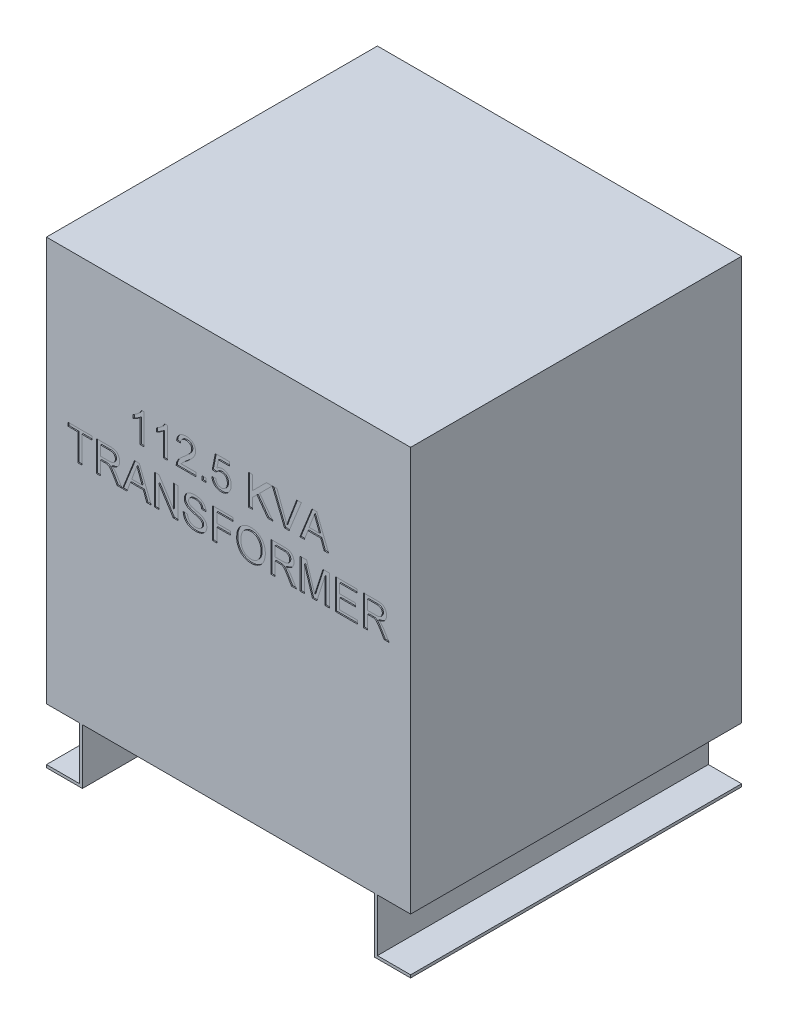
SolidWorks part; units mm, degrees
ref_plane "Front" through (0, 0, 0) normal (0, 0, 1) x (1, 0, 0)
ref_plane "Top" through (0, 0, 0) normal (0, 1, 0) x (1, 0, 0)
ref_plane "Right" through (0, 0, 0) normal (1, 0, 0) x (0, 0, -1)
sketch "Sketch1" plane through (0, 0, 0) normal (0, 1, 0) x (1, 0, 0)
  line L1 (-417.83, 379.73) -> (417.83, 379.73)
  line L2 (-417.83, 379.73) -> (-417.83, -379.73)
  line L3 (-417.83, -379.73) -> (417.83, -379.73)
  line L4 (417.83, 379.73) -> (417.83, -379.73)
  line L5 (-417.83, 379.73) -> (417.83, -379.73) construction
  line L6 (-417.83, -379.73) -> (417.83, 379.73) construction
  point P0 (0, 0)
  dimension "D1" = 835.66
  dimension "D2" = 759.46
extrude "Boss-Extrude1" add sketch "Sketch1" along normal blind 1054.608
sketch "Sketch2" plane through (0, 0, 379.73) normal (0, 0, 1) x (1, 0, 0)
  line L0 (0, 0) -> (0, 63.5) construction
  line L1 (-417.83, 0) -> (417.83, 0) construction
  line L2 (-335.28, 127) -> (335.28, 127)
  line L3 (-335.28, 127) -> (-335.28, 0)
  line L4 (-335.28, 0) -> (335.28, 0)
  line L5 (335.28, 127) -> (335.28, 0)
  line L6 (-335.28, 127) -> (335.28, 0) construction
  line L7 (-335.28, 0) -> (335.28, 127) construction
  line L8 (-417.83, 1054.608) -> (-417.83, 0) construction
  line L9 (-417.83, 6.35) -> (-341.63, 6.35)
  line L10 (-417.83, 6.35) -> (-417.83, 127)
  line L11 (-417.83, 127) -> (-341.63, 127)
  line L12 (-341.63, 6.35) -> (-341.63, 127)
  line L13 (417.83, 1054.608) -> (417.83, 0) construction
  line L14 (417.83, 6.35) -> (341.63, 6.35)
  line L15 (417.83, 6.35) -> (417.83, 127)
  line L16 (417.83, 127) -> (341.63, 127)
  line L17 (341.63, 6.35) -> (341.63, 127)
  line L18 (-417.83, 6.35) -> (-417.83, 0) construction
  line L19 (-341.63, 6.35) -> (-335.28, 6.35) construction
  line L20 (341.63, 6.35) -> (335.28, 6.35) construction
  dimension "D1" = 6.35
  dimension "D2" = 76.2
  dimension "D3" = 127
extrude "Cut-Extrude1" cut sketch "Sketch2" against normal through all
sketch "Sketch3" plane through (0, 0, 379.73) normal (0, 0, 1) x (1, 0, 0)
  line L0 (-417.83, 749.808) -> (417.83, 749.808) construction
  line L1 (417.83, 1054.608) -> (417.83, 127) construction
  line L2 (-417.83, 1054.608) -> (417.83, 1054.608) construction
  line L3 (-417.83, 1054.608) -> (-417.83, 127) construction
  text T0 "112.5 KVA\r\nTRANSFORMER" font "Arial" height in points 270
  dimension "D1" = 304.8
extrude "Cut-Extrude2" cut sketch "Sketch3" against normal blind 2.54
